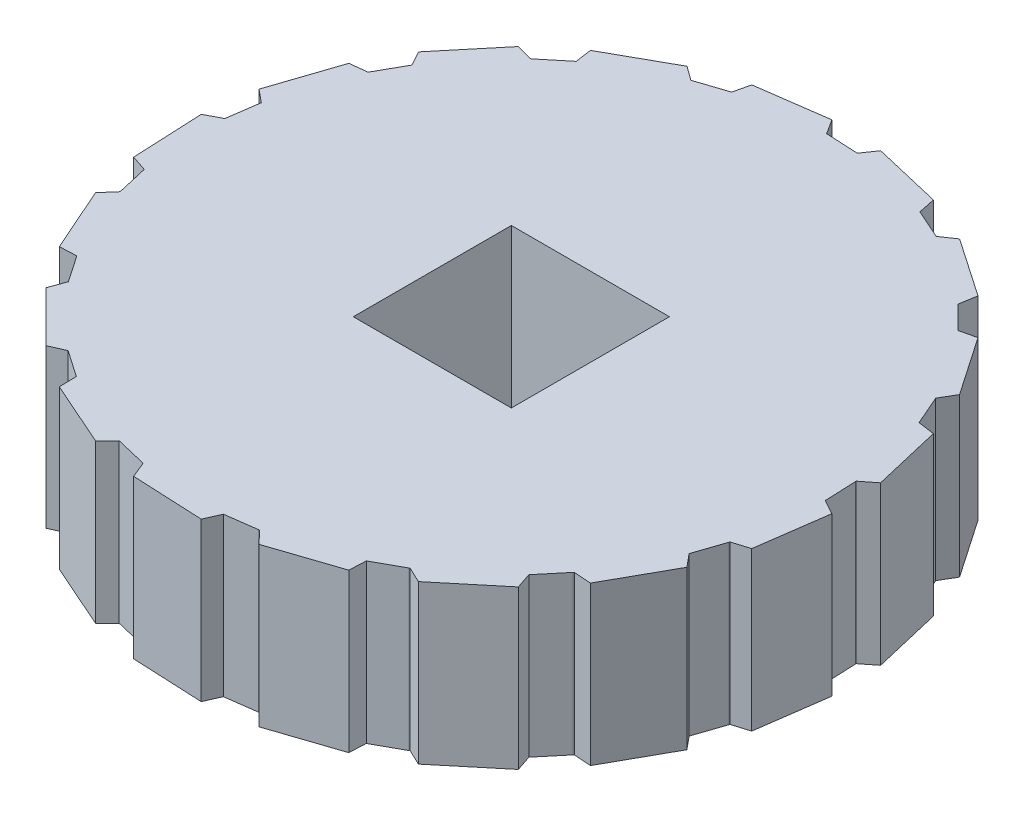
SolidWorks part; units mm, degrees
ref_plane "Front Plane" through (0, 0, 0) normal (0, 0, 1) x (1, 0, 0)
ref_plane "Top Plane" through (0, 0, 0) normal (0, 1, 0) x (1, 0, 0)
ref_plane "Right Plane" through (0, 0, 0) normal (1, 0, 0) x (0, 0, -1)
sketch "Belt Pulley" plane through (0, 0, 0) normal (0, 1, 0) x (1, 0, 0)
  line L0 (0, -18.2889) -> (0, 17.4478) construction
  line L1 (-3.175, -3.175) -> (3.175, -3.175)
  line L2 (-3.175, -3.175) -> (-3.175, 3.175)
  line L3 (-3.175, 3.175) -> (3.175, 3.175)
  line L4 (3.175, -3.175) -> (3.175, 3.175)
  line L5 (-3.175, -3.175) -> (3.175, 3.175) construction
  line L6 (-3.175, 3.175) -> (3.175, -3.175) construction
  line L7 (0, 12.7) -> (1.26, 12.6373)
  line L8 (1.26, 12.6373) -> (0, 0) construction
  line L9 (1.26, 12.6373) -> (1.64, 13.1935) construction
  line L10 (1.64, 13.1935) -> (4.4143, 12.5408)
  line L11 (4.4143, 12.5408) -> (4.7709, 12.4095) construction
  line L12 (0, 0) -> (4.7709, 12.4095) construction
  line L13 (8.6464, 10.0993) -> (8.5318, 9.4073)
  line L14 (1.26, 12.6373) -> (1.64, 13.1935)
  line L15 (4.4143, 12.5408) -> (4.5573, 11.8541)
  line L16 (6.2953, 11.7101) -> (8.6464, 10.0993)
  line L17 (5.74, 11.3288) -> (6.2953, 11.7101)
  line L18 (4.5878, 11.8424) -> (5.74, 11.3288)
  line L19 (11.7109, 6.2939) -> (11.354, 5.69)
  line L20 (10.1004, 8.6452) -> (11.7109, 6.2939)
  line L21 (9.4449, 8.4903) -> (10.1004, 8.6452)
  line L22 (8.5559, 9.3854) -> (9.4449, 8.4903)
  line L23 (13.1937, 1.6384) -> (12.6428, 1.2043)
  line L24 (12.5413, 4.4128) -> (13.1937, 1.6384)
  line L25 (11.8741, 4.505) -> (12.5413, 4.4128)
  line L26 (11.3686, 5.6609) -> (11.8741, 4.505)
  line L27 (12.8946, -3.2383) -> (12.2241, -3.4441)
  line L28 (13.2885, -0.4157) -> (12.8946, -3.2383)
  line L29 (12.6997, -0.0886) -> (13.2885, -0.4157)
  line L30 (12.6458, 1.1718) -> (12.6997, -0.0886)
  line L31 (10.854, -7.6777) -> (10.1544, -7.6274)
  line L32 (12.241, -5.188) -> (10.854, -7.6777)
  line L33 (11.8101, -4.6703) -> (12.241, -5.188)
  line L34 (12.2152, -3.4755) -> (11.8101, -4.6703)
  line L35 (7.3476, -11.0802) -> (6.7134, -10.7806)
  line L36 (9.5403, -9.2596) -> (7.3476, -11.0802)
  line L37 (9.3255, -8.6212) -> (9.5403, -9.2596)
  line L38 (10.1348, -7.6535) -> (9.3255, -8.6212)
  line L39 (2.8488, -12.9862) -> (2.3657, -12.4777)
  line L40 (5.5511, -12.0807) -> (2.8488, -12.9862)
  line L41 (5.5814, -11.4078) -> (5.5511, -12.0807)
  line L42 (6.6857, -10.7978) -> (5.5814, -11.4078)
  line L43 (-2.0347, -13.1384) -> (-2.3016, -12.4897)
  line L44 (0.8122, -13.2702) -> (-2.0347, -13.1384)
  line L45 (1.0836, -12.6537) -> (0.8122, -13.2702)
  line L46 (2.3336, -12.4838) -> (1.0836, -12.6537)
  line L47 (-6.6435, -11.5161) -> (-6.6579, -10.8149)
  line L48 (-4.0364, -12.6675) -> (-6.6435, -11.5161)
  line L49 (-3.5607, -12.1906) -> (-4.0364, -12.6675)
  line L50 (-2.3336, -12.4838) -> (-3.5607, -12.1906)
  line L51 (-10.355, -8.3386) -> (-10.1151, -7.6795)
  line L52 (-8.3398, -10.354) -> (-10.355, -8.3386)
  line L53 (-7.724, -10.0812) -> (-8.3398, -10.354)
  line L54 (-6.6857, -10.7978) -> (-7.724, -10.0812)
  line L55 (-12.6679, -4.0349) -> (-12.2062, -3.5069)
  line L56 (-11.5169, -6.6421) -> (-12.6679, -4.0349)
  line L57 (-10.8441, -6.6102) -> (-11.5169, -6.6421)
  line L58 (-10.1348, -7.6535) -> (-10.8441, -6.6102)
  line L59 (-13.2701, 0.8138) -> (-12.6488, 1.1393)
  line L60 (-13.1386, -2.0332) -> (-13.2701, 0.8138)
  line L61 (-12.4997, -2.2465) -> (-13.1386, -2.0332)
  line L62 (-12.2152, -3.4755) -> (-12.4997, -2.2465)
  line L63 (-12.08, 5.5525) -> (-11.3831, 5.6317)
  line L64 (-12.9859, 2.8503) -> (-12.08, 5.5525)
  line L65 (-12.4672, 2.4207) -> (-12.9859, 2.8503)
  line L66 (-12.6458, 1.1718) -> (-12.4672, 2.4207)
  line L67 (-9.2584, 9.5414) -> (-8.58, 9.3634)
  line L68 (-11.0793, 7.3489) -> (-9.2584, 9.5414)
  line L69 (-10.7509, 6.7609) -> (-11.0793, 7.3489)
  line L70 (-11.3686, 5.6609) -> (-10.7509, 6.7609)
  line L71 (-5.1865, 12.2416) -> (-4.6182, 11.8306)
  line L72 (-7.6764, 10.8549) -> (-5.1865, 12.2416)
  line L73 (-7.5826, 10.188) -> (-7.6764, 10.8549)
  line L74 (-8.5559, 9.3854) -> (-7.5826, 10.188)
  line L75 (-0.4141, 13.2886) -> (-0.0326, 12.7)
  line L76 (-3.2368, 12.895) -> (-0.4141, 13.2886)
  line L77 (-3.3902, 12.2391) -> (-3.2368, 12.895)
  line L78 (-4.5878, 11.8424) -> (-3.3902, 12.2391)
  arc A0 (0, 12.7) -> (-0.0326, 12.7) centre (0, 0) ccw
  circle A1 centre (0, 0) radius 13.295 construction
  arc A2 (-3.3902, 12.2391) -> (-4.6182, 11.8306) centre (0, 0) ccw
  arc A3 (-7.5826, 10.188) -> (-8.58, 9.3634) centre (0, 0) ccw
  arc A4 (5.74, 11.3288) -> (4.5573, 11.8541) centre (0, 0) ccw
  arc A5 (9.4449, 8.4903) -> (8.5318, 9.4073) centre (0, 0) ccw
  arc A6 (11.8741, 4.505) -> (11.354, 5.69) centre (0, 0) ccw
  arc A7 (12.6997, -0.0886) -> (12.6428, 1.2043) centre (0, 0) ccw
  arc A8 (11.8101, -4.6703) -> (12.2241, -3.4441) centre (0, 0) ccw
  arc A9 (-10.7509, 6.7609) -> (-11.3831, 5.6317) centre (0, 0) ccw
  arc A10 (-12.4672, 2.4207) -> (-12.6488, 1.1393) centre (0, 0) ccw
  arc A11 (-12.4997, -2.2465) -> (-12.2062, -3.5069) centre (0, 0) ccw
  arc A12 (-10.8441, -6.6102) -> (-10.1151, -7.6795) centre (0, 0) ccw
  arc A13 (-7.724, -10.0812) -> (-6.6579, -10.8149) centre (0, 0) ccw
  arc A14 (-3.5607, -12.1906) -> (-2.3016, -12.4897) centre (0, 0) ccw
  arc A15 (1.0836, -12.6537) -> (2.3657, -12.4777) centre (0, 0) ccw
  arc A16 (5.5814, -11.4078) -> (6.7134, -10.7806) centre (0, 0) ccw
  arc A17 (9.3255, -8.6212) -> (10.1544, -7.6274) centre (0, 0) ccw
  point P98 (0, 0)
  dimension "D1" = 25.4
  dimension "D9" = 26.59
  dimension "D2" = 6.35
  dimension "D3" = 6.35
  dimension "D4" = 0.38
  dimension "D5" = 2.85
  dimension "D6" = 1.26
  dimension "D7" = 0.38
  dimension "D8" = 17
extrude "Boss-Extrude1" add sketch "Belt Pulley" along normal blind 6.35 contours A0 L4 L1 L2 L3
equation "\"Ball Diameter\"= 1.75in"
equation "\"Sheet Thickness\"= 0.25in"
equation "\"Screw Diameter\"= .17in"
equation "\"Robot Diameter\"= 14in"
equation "\"Castor Screw Diameter\"= 0.22in"
equation "\"Wheel Diameter\" = 4in"
equation "\"Nut Diameter\" = 8.4mm"
equation "\"Nut Height\" = 2.9mm"
equation "\"Screw Height\" = 0.55in"
equation "\"Pulley Diameter\" = 1in"
equation "\"Reactor Height\" = 14in"
equation "\"D1@Belt Pulley\"=\"Pulley Diameter\""
equation "\"D2@Belt Pulley\"=\"Sheet Thickness\""
equation "\"D3@Belt Pulley\"=\"Sheet Thickness\""
equation "\"D1@Boss-Extrude1\"=\"Sheet Thickness\""
equation "\"D9@Belt Pulley\" = \"Pulley Diameter\" + 1.19mm"
